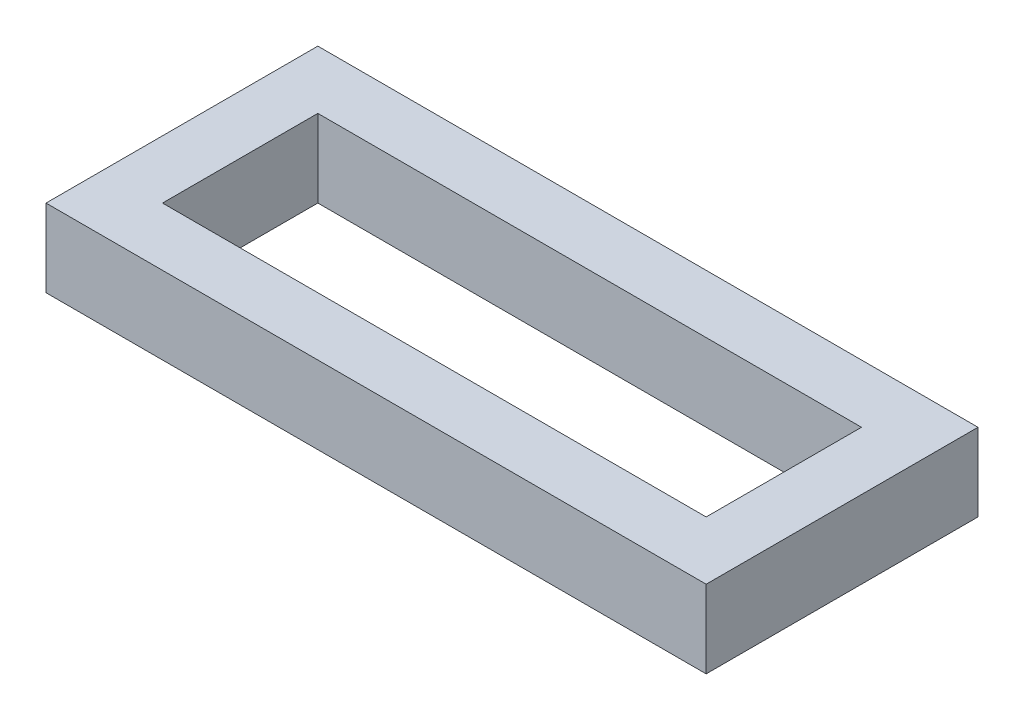
SolidWorks part; units mm, degrees
ref_plane "Front Plane" through (0, 0, 0) normal (0, 0, 1) x (1, 0, 0)
ref_plane "Top Plane" through (0, 0, 0) normal (0, 1, 0) x (1, 0, 0)
ref_plane "Right Plane" through (0, 0, 0) normal (1, 0, 0) x (0, 0, -1)
sketch "Sketch1" plane through (0, 0, 0) normal (0, 1, 0) x (1, 0, 0)
  line L0 (-110.5607, 0) -> (141.5265, 0) construction
  line L1 (0, 72.5078) -> (0, -80.1402) construction
  line L3 (-70, 20) -> (70, 20)
  line L4 (-70, 20) -> (-70, -20)
  line L5 (-70, -20) -> (70, -20)
  line L6 (70, 20) -> (70, -20)
  line L7 (-70, 20) -> (70, -20) construction
  line L8 (-70, -20) -> (70, 20) construction
  line L9 (-85, 35) -> (85, 35)
  line L10 (-85, 35) -> (-85, -35)
  line L11 (-85, -35) -> (85, -35)
  line L12 (85, 35) -> (85, -35)
  line L13 (-85, 35) -> (85, -35) construction
  line L14 (-85, -35) -> (85, 35) construction
  point P5 (0, 0)
  point P10 (0, 0)
  dimension "D1" = 70
  dimension "D2" = 40
  dimension "D3" = 170
  dimension "D4" = 140
extrude "Boss-Extrude1" add sketch "Sketch1" along normal blind 20
